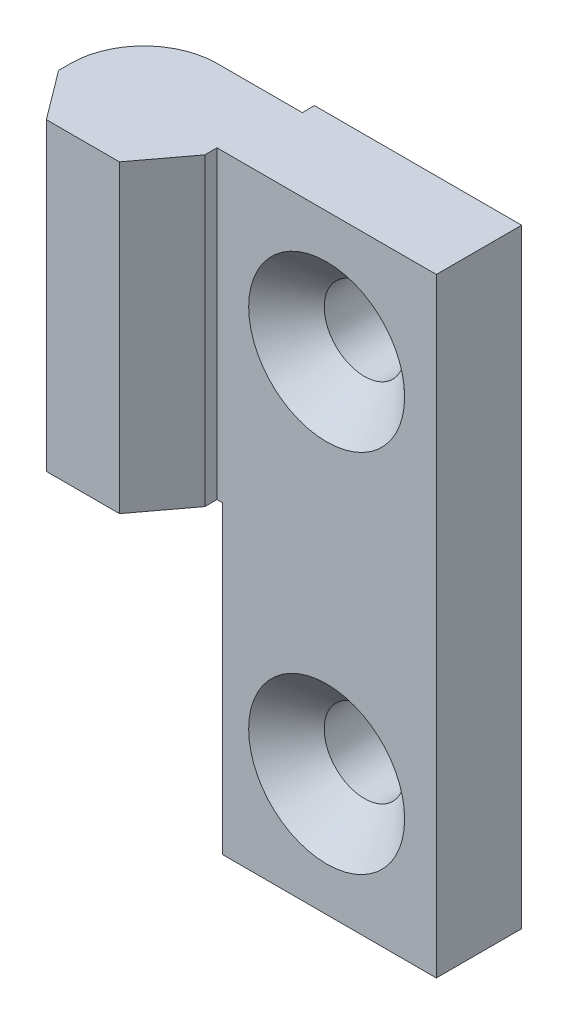
SolidWorks part; units mm, degrees
ref_plane "前视基准面" through (0, 0, 0) normal (0, 0, 1) x (1, 0, 0)
ref_plane "上视基准面" through (0, 0, 0) normal (0, 1, 0) x (1, 0, 0)
ref_plane "右视基准面" through (0, 0, 0) normal (1, 0, 0) x (0, 0, -1)
sketch "草图1" plane through (0, 0, 0) normal (0, 1, 0) x (1, 0, 0)
  line L0 (0, 0) -> (-18, 0)
  line L1 (-18, 0) -> (-18, -1)
  line L2 (-18, -1) -> (-21, -5)
  line L3 (-21, -5) -> (-27, -5)
  line L4 (-27, -5) -> (-30, -1)
  line L5 (-30, -1) -> (-30, 6)
  line L6 (-30, 6) -> (-17, 6)
  line L7 (-17, 6) -> (-17, 7)
  line L8 (-17, 7) -> (0, 7)
  line L9 (0, 7) -> (0, 0)
  line L10 (-24, -5) -> (-24, 1.1679) construction
  dimension "D1" = 7
  dimension "D2" = 18
  dimension "D3" = 4
  dimension "D4" = 6
  dimension "D5" = 1
  dimension "D6" = 17
  dimension "D7" = 30
  dimension "D8" = 12
extrude "凸台-拉伸1" add sketch "草图1" along normal blind 50
fillet "圆角1" radius 6 1 edges at (-30, 25, -6)
sketch "草图2" plane through (0, 0, 5) normal (0, 0, 1) x (1, 0, 0)
  line L0 (-18, 50) -> (-18, 0) construction
  line L1 (-30, 0) -> (-18, 0)
  line L2 (-30, 0) -> (-30, 25)
  line L3 (-30, 25) -> (-18, 25)
  line L4 (-18, 0) -> (-18, 25)
  line L5 (-27, 50) -> (-21, 50) construction
  dimension "D1" = 25
hole_wizard "打孔尺寸根据内六角花形半沉头螺钉的类型1" positions "草图4" profile "草图3" countersink size "M6" standard "GB" end condition through all
sketch "草图4" plane through (0, 0, 0) normal (0, 0, 1) x (1, 0, 0)
  line L0 (0, 25) -> (-21.0906, 25) construction
  line L1 (0, 50) -> (0, 0) construction
  point P0 (-9, 40)
  point P1 (-9, 10)
  dimension "D1" = 30
  dimension "D2" = 15
sketch "草图3" plane through (-9, 40, 0) normal (1, 0, 0) x (0, -1, 0)
  line L0 (0, 0) -> (0, 7)
  line L1 (0, 7) -> (3.3, 7)
  line L2 (3.3, 7) -> (3.3, 3.1)
  line L3 (3.3, 3.1) -> (6.4, 0)
  line L5 (6.4, 0) -> (0, 0)
  line L6 (-3.3, 3.1) -> (-6.4, 0) construction
  line L11 (0, -6.35) -> (0, 107.95) construction
  dimension "通孔孔直径" = 6.6
  dimension "通孔孔深度" = 7
  dimension "近端锥形沉头孔直径" = 12.8
  dimension "近端锥形沉头孔角度" = 90
sketch "草图5" plane through (0, 0, -6) normal (0, 0, -1) x (-1, 0, 0)
  line L1 (30, 25) -> (17, 25)
  line L2 (30, 25) -> (30, 0)
  line L3 (30, 0) -> (17, 0)
  line L4 (17, 25) -> (17, 0)
loft "切除-放样1" cut profiles "草图2", "草图5"
